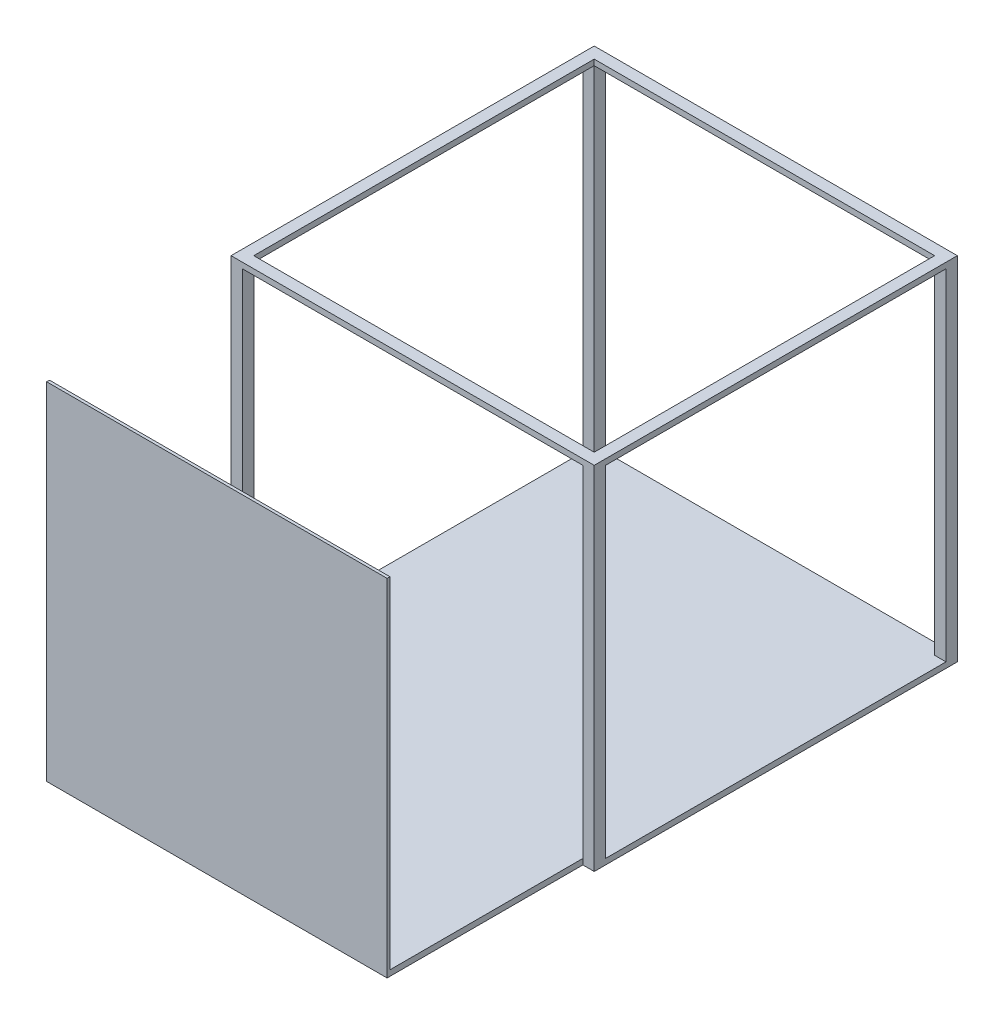
SolidWorks part; units mm, degrees
ref_plane "Front Plane" through (0, 0, 0) normal (0, 0, 1) x (1, 0, 0)
ref_plane "Top Plane" through (0, 0, 0) normal (0, 1, 0) x (1, 0, 0)
ref_plane "Right Plane" through (0, 0, 0) normal (1, 0, 0) x (0, 0, -1)
sketch "Sketch1" plane through (0, 0, 0) normal (0, 1, 0) x (1, 0, 0)
  line L1 (-203.2, -203.2) -> (203.2, -203.2)
  line L2 (-203.2, -203.2) -> (-203.2, 203.2)
  line L3 (-203.2, 203.2) -> (203.2, 203.2)
  line L4 (203.2, -203.2) -> (203.2, 203.2)
  line L5 (-203.2, -203.2) -> (203.2, 203.2) construction
  line L6 (-203.2, 203.2) -> (203.2, -203.2) construction
  point P0 (0, 0)
  dimension "D1" = 406.4
  dimension "D2" = 406.4
extrude "Boss-Extrude1" add sketch "Sketch1" along normal blind 6.35
sketch "Sketch2" plane through (0, 6.35, 0) normal (0, 1, 0) x (1, 0, 0)
  line L0 (0, 203.2) -> (0, -203.2) construction
  line L1 (-203.2, 203.2) -> (-190.5, 203.2)
  line L2 (-203.2, 203.2) -> (-203.2, 190.5)
  line L3 (-203.2, 190.5) -> (-190.5, 190.5)
  line L4 (-190.5, 203.2) -> (-190.5, 190.5)
  line L5 (203.2, 203.2) -> (-203.2, 203.2) construction
  line L6 (-203.2, -203.2) -> (203.2, -203.2) construction
  line L7 (-203.2, 0) -> (203.2, 0) construction
  line L8 (-203.2, 203.2) -> (-203.2, -203.2) construction
  line L9 (203.2, -203.2) -> (203.2, 203.2) construction
  line L10 (190.5, 203.2) -> (190.5, 190.5)
  line L11 (203.2, 190.5) -> (190.5, 190.5)
  line L12 (203.2, 203.2) -> (203.2, 190.5)
  line L13 (203.2, 203.2) -> (190.5, 203.2)
  line L14 (203.2, -203.2) -> (190.5, -203.2)
  line L15 (203.2, -203.2) -> (203.2, -190.5)
  line L16 (203.2, -190.5) -> (190.5, -190.5)
  line L17 (190.5, -203.2) -> (190.5, -190.5)
  line L18 (-190.5, -203.2) -> (-190.5, -190.5)
  line L19 (-203.2, -190.5) -> (-190.5, -190.5)
  line L20 (-203.2, -203.2) -> (-203.2, -190.5)
  line L21 (-203.2, -203.2) -> (-190.5, -203.2)
  dimension "D1" = 12.7
  dimension "D2" = 12.7
extrude "Boss-Extrude2" add sketch "Sketch2" along normal blind 381
sketch "Sketch3" plane through (0, 387.35, 0) normal (0, 1, 0) x (1, 0, 0)
  line L0 (203.2, -190.5) -> (190.5, -190.5) construction
  line L1 (-203.2, 203.2) -> (203.2, 203.2)
  line L2 (-203.2, 203.2) -> (-203.2, -203.2)
  line L3 (-203.2, -203.2) -> (203.2, -203.2)
  line L4 (203.2, 203.2) -> (203.2, -203.2)
  line L5 (-190.5, 190.5) -> (190.5, 190.5)
  line L6 (-190.5, 190.5) -> (-190.5, -190.5)
  line L7 (-190.5, -190.5) -> (190.5, -190.5)
  line L8 (190.5, 190.5) -> (190.5, -190.5)
  line L9 (190.5, -190.5) -> (190.5, -203.2) construction
extrude "Boss-Extrude3" add sketch "Sketch3" along normal blind 6.35
sketch "Sketch4" plane through (0, 6.35, 0) normal (0, 1, 0) x (1, 0, 0)
  line L0 (190.5, -190.5) -> (190.5, -203.2) construction
  line L1 (-190.5, -190.5) -> (190.5, -190.5)
  line L2 (-190.5, -190.5) -> (-190.5, -419.1)
  line L3 (-190.5, -419.1) -> (190.5, -419.1)
  line L4 (190.5, -190.5) -> (190.5, -419.1)
  line L5 (-203.2, 190.5) -> (-190.5, 190.5) construction
  dimension "D1" = 609.6
extrude "Boss-Extrude4" add sketch "Sketch4" against normal blind 6.35
ref_plane "Plane1" through (0, 793.75, 0) normal (0, 1, 0) x (1, 0, 0)
sketch "Sketch5" plane through (0, 793.75, 0) normal (0, 1, 0) x (1, 0, 0)
  line L0 (-190.5, -419.1) -> (190.5, -419.1) construction
  line L1 (-203.2, 203.2) -> (203.2, 203.2)
  line L2 (-203.2, 203.2) -> (-203.2, -431.8)
  line L3 (-203.2, -431.8) -> (203.2, -431.8)
  line L4 (203.2, 203.2) -> (203.2, -431.8)
  line L6 (-190.5, 190.5) -> (190.5, 190.5)
  line L7 (-190.5, 190.5) -> (-190.5, -419.1)
  line L8 (-190.5, -419.1) -> (190.5, -419.1)
  line L9 (190.5, 190.5) -> (190.5, -419.1)
  dimension "D1" = 12.7
extrude "Boss-Extrude5" [suppressed] add sketch "Sketch5" along normal blind 6.35 separate body
sketch "Sketch6" plane through (0, 0, 419.1) normal (0, 0, 1) x (1, 0, 0)
  line L1 (-190.5, 0) -> (190.5, 0)
  line L2 (-190.5, 0) -> (-190.5, 387.35)
  line L3 (-190.5, 387.35) -> (190.5, 387.35)
  line L4 (190.5, 0) -> (190.5, 387.35)
extrude "Boss-Extrude6" add sketch "Sketch6" along normal blind 3.175
